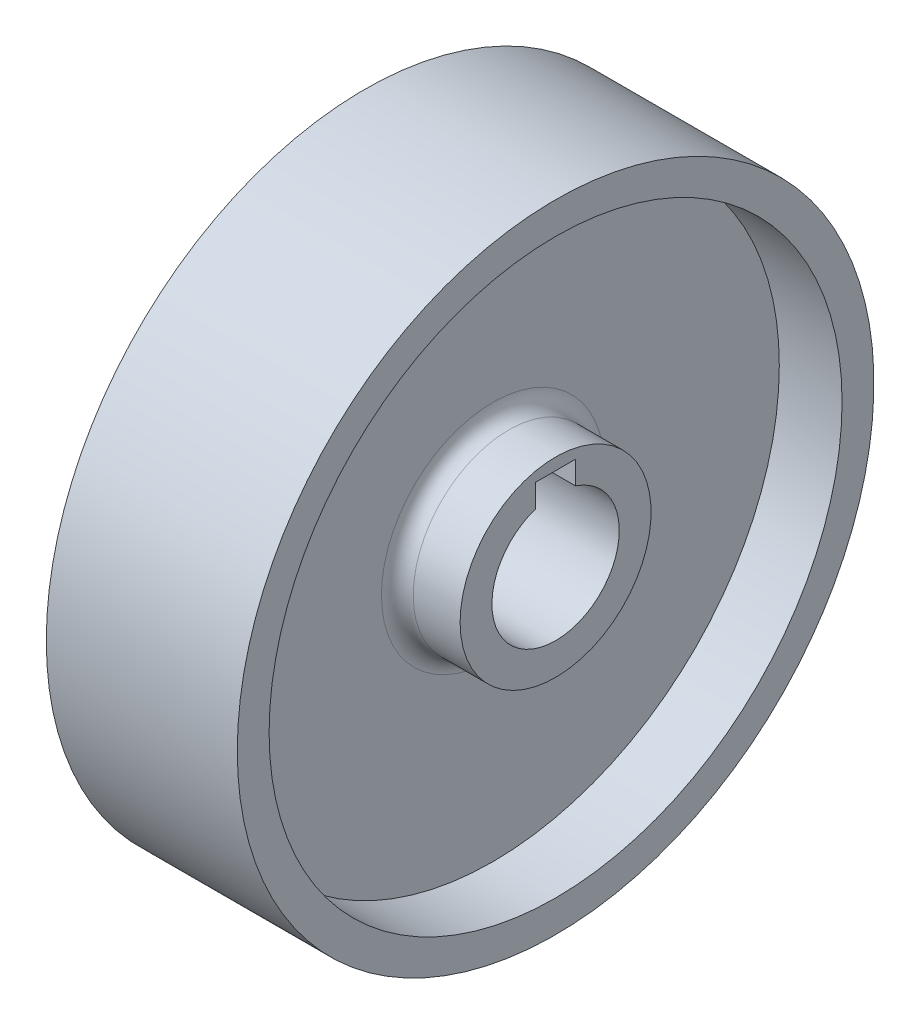
SolidWorks part; units mm, degrees
ref_plane "Front Plane" through (0, 0, 0) normal (0, 0, 1) x (1, 0, 0)
ref_plane "Top Plane" through (0, 0, 0) normal (0, 1, 0) x (1, 0, 0)
ref_plane "Right Plane" through (0, 0, 0) normal (1, 0, 0) x (0, 0, -1)
sketch "Sketch1" plane through (0, 0, 0) normal (0, 0, 1) x (1, 0, 0)
  line L0 (0, -18.4571) -> (0, -26.4571) construction
  line L1 (-12.1143, 13.5429) -> (11.8857, 13.5429)
  line L2 (11.8857, 13.5429) -> (11.8857, 9.5429)
  line L3 (11.8857, 9.5429) -> (4, 9.5429)
  line L4 (4, 9.5429) -> (4, -14.4571)
  line L5 (4, -14.4571) -> (11.8857, -14.4571)
  line L6 (11.8857, -14.4571) -> (11.8857, -18.4571)
  line L7 (11.8857, -18.4571) -> (-12.1143, -18.4571)
  line L8 (-12.1143, -18.4571) -> (-12.1143, -14.4571)
  line L9 (-12.1143, -14.4571) -> (-4, -14.4571)
  line L10 (-4, -14.4571) -> (-4, 9.5429)
  line L11 (-4, 9.5429) -> (-12.1143, 9.5429)
  line L12 (-12.1143, 9.5429) -> (-12.1143, 12.7429)
  line L13 (-20.4571, -26.4571) -> (30.2857, -26.4571) construction
  line L14 (-12.1143, 13.5429) -> (-12.1143, 12.7429)
  dimension "D1" = 4
  dimension "D2" = 4
  dimension "D3" = 24
  dimension "D4" = 24
  dimension "D5" = 40
  dimension "D6" = 8
  dimension "D7" = 4
  dimension "D8" = 4
revolve "Revolve1" add sketch "Sketch1" angle 360 about L13
ref_plane "Plane1" through (12, 0, 0) normal (1, 0, 0) x (0, 0, -1)
sketch "Sketch2" plane through (12, 0, 0) normal (1, 0, 0) x (0, 0, -1)
  line L0 (0, -15.9571) -> (0, -20.4216) construction
  line L1 (-2.5, -20.4216) -> (-2.5, -15.9571)
  line L2 (-2.5, -15.9571) -> (2.5, -15.9571)
  line L3 (2.5, -15.9571) -> (2.5, -20.4216)
  line L4 (-2.5, -20.4216) -> (2.5, -20.4216)
  circle A0 centre (0, -26.4571) radius 8 construction
  dimension "D3" = 10.5
  dimension "D1" = 5
  dimension "D2" = 2.5
extrude "Cut-Extrude1" cut sketch "Sketch2" against normal through all
fillet "Fillet1" radius 2 1 edges at (4, -26.4571, 12)
fillet "Fillet2" radius 2 1 edges at (-4, -26.4571, 12)
